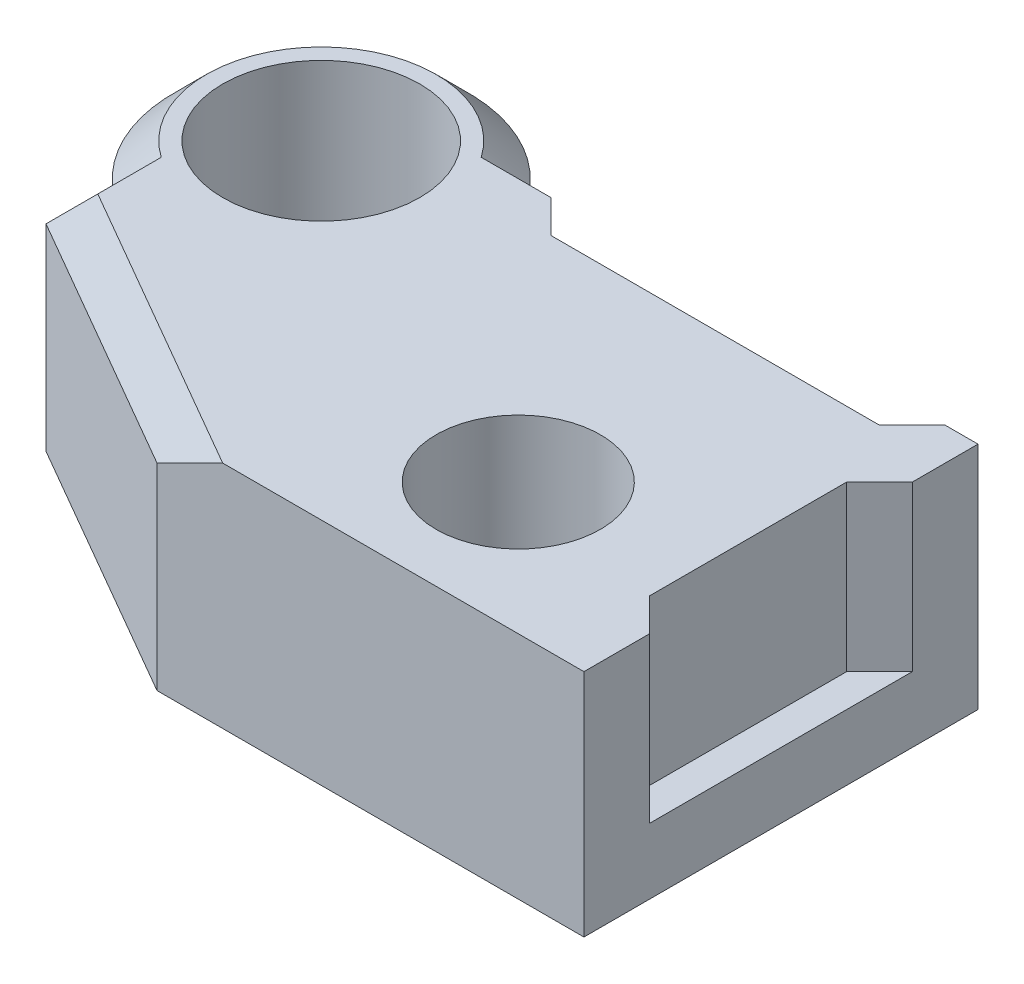
SolidWorks part; units mm, degrees
ref_plane "Front Plane" through (0, 0, 0) normal (0, 0, 1) x (1, 0, 0)
ref_plane "Top Plane" through (0, 0, 0) normal (0, 1, 0) x (1, 0, 0)
ref_plane "Right Plane" through (0, 0, 0) normal (1, 0, 0) x (0, 0, -1)
sketch "Sketch1" plane through (0, 0, 0) normal (0, 1, 0) x (1, 0, 0)
  line L0 (-40, -16.906) -> (0, -40)
  line L1 (-4.8444, 20) -> (65, 20)
  line L2 (-40, -6.7705) -> (-40, -16.906)
  line L3 (0, -40) -> (65, -40)
  line L4 (65, 20) -> (65, -40)
  line L5 (0, 0) -> (0, -40) construction
  arc A0 (-4.8444, 20) -> (-40, -6.7705) centre (-25, 10) ccw
  point P2 (-40, -11.8382)
  dimension "D5" = 45
  dimension "D1" = 10
  dimension "D2" = 60
  dimension "D3" = 40
  dimension "D4" = 90
  dimension "D6" = 150
  dimension "D7" = 40
  dimension "D8" = 105
extrude "Boss-Extrude1" add sketch "Sketch1" along normal blind 35 contours A0 L2 L0 L3 L4 L1
sketch "Sketch2" plane through (0, 0, 0) normal (0, 1, 0) x (1, 0, 0)
  circle A0 centre (35, -20) radius 12.5
  circle A1 centre (-25, 10) radius 15
  dimension "D3" = 25
  dimension "D4" = 30
  dimension "D1" = 35
  dimension "D2" = 20
extrude "Cut-Extrude3" cut sketch "Sketch2" against normal through all and the other way through all contours A0
sketch "Sketch3" plane through (0, 0, 0) normal (0, 1, 0) x (1, 0, 0)
  line L0 (-4.8444, 20) -> (65, 20) construction
  line L1 (0, 20) -> (60, 20)
  line L3 (5, 15) -> (55, 15)
  line L5 (65, 20) -> (65, -40) construction
  line L7 (65, 10) -> (65, -30)
  line L9 (60, 5) -> (60, -25)
  line L10 (5, 15) -> (0, 20)
  line L11 (55, 15) -> (60, 20)
  line L12 (60, 5) -> (65, 10)
  line L13 (60, -25) -> (65, -30)
  point P0 (65, 7.552)
  dimension "D1" = 50
  dimension "D2" = 45
  dimension "D3" = 45
  dimension "D4" = 5
  dimension "D5" = 5
  dimension "D6" = 5
  dimension "D7" = 45
  dimension "D8" = 30
  dimension "D9" = 10
  dimension "D10" = 45
extrude "Cut-Extrude4" cut sketch "Sketch3" along normal up to surface (25 mm away) from offset 10 contours L9 L13 L7 L12
chamfer "Chamfer1" distance 5 angle 45 3 edges at (-38.6312, 35, -27.9008) (-40, 35, 11.8382) (-20, 35, 28.453)
